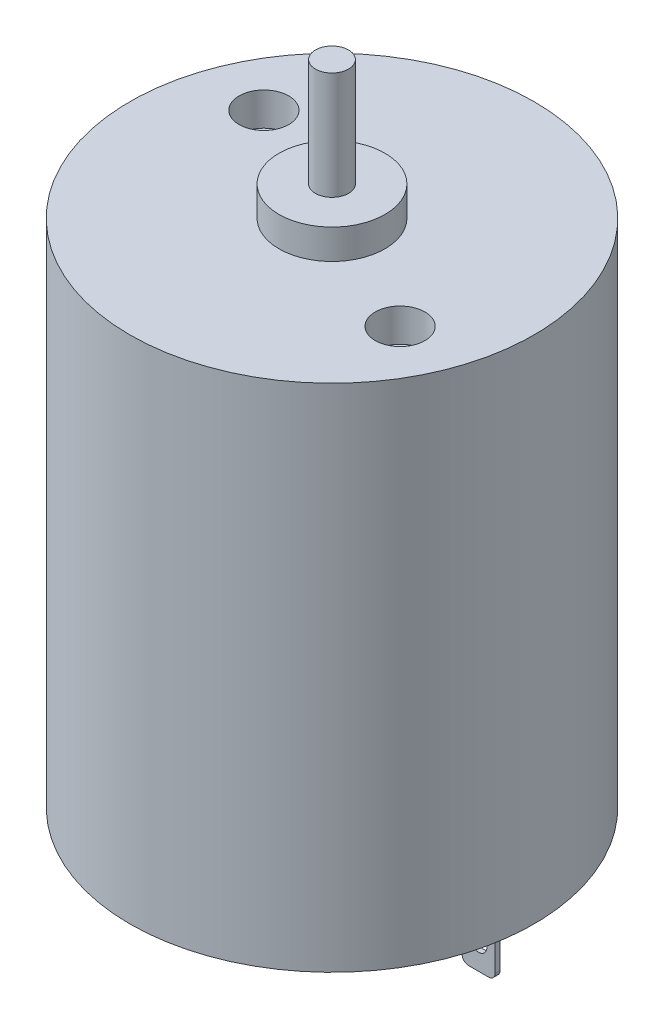
SolidWorks part; units mm, degrees
ref_plane "前视基准面" through (0, 0, 0) normal (0, 0, 1) x (1, 0, 0)
ref_plane "上视基准面" through (0, 0, 0) normal (0, 1, 0) x (1, 0, 0)
ref_plane "右视基准面" through (0, 0, 0) normal (1, 0, 0) x (0, 0, -1)
other "Configuration Table"
sketch "草图1" plane through (0, 0, 0) normal (0, 1, 0) x (1, 0, 0)
  circle A0 centre (0, 0) radius 12.2
  dimension "D1" = 24.4
extrude "凸台-拉伸1" add sketch "草图1" along normal blind 30.8
sketch "草图2" plane through (0, 30.8, 0) normal (0, 1, 0) x (1, 0, 0)
  circle A0 centre (0, 0) radius 3.2
  dimension "D1" = 6.4
extrude "凸台-拉伸2" add sketch "草图2" along normal blind 1.8
sketch "草图3" plane through (0, 32.6, 0) normal (0, 1, 0) x (1, 0, 0)
  circle A0 centre (0, 0) radius 1
  dimension "D1" = 2
extrude "凸台-拉伸3" add sketch "草图3" along normal blind 6.5
sketch "草图4" plane through (0, 30.8, 0) normal (0, 1, 0) x (1, 0, 0)
  line L0 (-7.7036, 3.5923) -> (7.7036, -3.5923) construction
  line L1 (12.2, 0) -> (-12.2, 0) construction
  line L2 (0, 12.2) -> (0, -12.2) construction
  circle A0 centre (0, 0) radius 12.2 construction
  circle A1 centre (7.7036, -3.5923) radius 1.5
  circle A2 centre (-7.7036, 3.5923) radius 1.5
  point P2 (0, 0)
  point P8 (0, 0)
  point P9 (0, 0)
  point P15 (0, 0)
  dimension "D2" = 3
  dimension "D1" = 8.5
  dimension "D3" = 2
  dimension "D4" = 25
extrude "切除-拉伸1" cut sketch "草图4" against normal blind 2
sketch "草图5" plane through (0, 0, 0) normal (0, -1, 0) x (1, 0, 0)
  line L1 (12.2, 0) -> (-12.2, 0) construction
  line L2 (-10, -0.15) -> (-8, -0.15)
  line L3 (-8, -0.15) -> (-8, 0.15)
  line L4 (-8, 0.15) -> (-10, 0.15)
  line L6 (-10, -0.15) -> (-10, 0.15)
  line L7 (10, -0.15) -> (8, -0.15)
  line L8 (0, 12.2) -> (0, -12.2) construction
  line L9 (8, -0.15) -> (8, 0.15)
  line L10 (8, 0.15) -> (10, 0.15)
  line L11 (10, -0.15) -> (10, 0.15)
  circle A0 centre (0, 0) radius 12.2 construction
  circle A1 centre (0, 0) radius 3.2
  dimension "D3" = 6.4
  dimension "D1" = 0.3
  dimension "D2" = 2
  dimension "D4" = 8
extrude "凸台-拉伸4" add sketch "草图5" along normal blind 1.6 contours A1 | L6 L4 L3 L2 | L7 L9 L10 L11
sketch "草图6" plane through (0, -1.6, 0) normal (0, -1, 0) x (1, 0, 0)
  line L4 (-10, -0.15) -> (-8, -0.15)
  line L5 (-8, -0.15) -> (-8, 0.15)
  line L6 (-8, 0.15) -> (-10, 0.15)
  line L7 (-10, 0.15) -> (-10, -0.15)
  line L8 (-10, -0.15) -> (-8, -0.15)
  line L9 (-8, -0.15) -> (-8, 0.15)
  line L10 (-8, 0.15) -> (-10, 0.15)
  line L11 (-10, 0.15) -> (-10, -0.15)
  line L12 (10, -0.15) -> (10, 0.15)
  line L13 (10, 0.15) -> (8, 0.15)
  line L14 (8, 0.15) -> (8, -0.15)
  line L15 (8, -0.15) -> (10, -0.15)
  line L16 (10, -0.15) -> (10, 0.15)
  line L17 (10, 0.15) -> (8, 0.15)
  line L18 (8, 0.15) -> (8, -0.15)
  line L19 (8, -0.15) -> (10, -0.15)
  dimension "D1" = 0
  dimension "D2" = 0
extrude "凸台-拉伸5" add sketch "草图6" along normal blind 2.4
sketch "草图7" plane through (0, -1.6, 0) normal (0, -1, 0) x (1, 0, 0)
  circle A0 centre (0, 0) radius 1
  dimension "D1" = 2
extrude "切除-拉伸2" cut sketch "草图7" against normal blind 2
sketch "草图8" plane through (0, 0, -0.15) normal (0, 0, -1) x (-1, 0, 0)
  line L0 (9, -4) -> (9, 0) construction
  line L1 (10, -4) -> (8, -4) construction
  line L2 (10, 0) -> (8, 0) construction
  line L3 (-8, -4) -> (8, -4) construction
  line L4 (0, -4) -> (0, 0) construction
  circle A0 centre (9, -2.5) radius 0.5
  circle A1 centre (-9, -2.5) radius 0.5
  point P13 (0, -4)
  dimension "D2" = 1
  dimension "D1" = 1.5
extrude "切除-拉伸4" cut sketch "草图8" against normal up to surface (0.3 mm away) up to face at (9, -2, 0.15)
fillet "圆角4" radius 0.4 4 edges at (-8, -4, 0) (-10, -4, 0) (8, -4, 0) (10, -4, 0)
